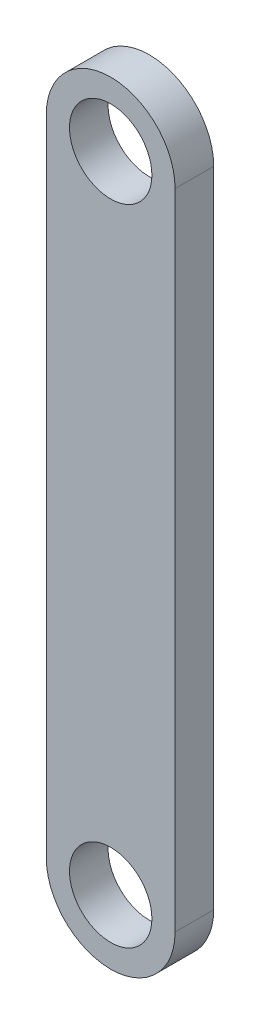
SolidWorks part; units mm, degrees
ref_plane "Plan de face" through (0, 0, 0) normal (0, 0, 1) x (1, 0, 0)
ref_plane "Plan de dessus" through (0, 0, 0) normal (0, 1, 0) x (1, 0, 0)
ref_plane "Plan de droite" through (0, 0, 0) normal (1, 0, 0) x (0, 0, -1)
sketch "Esquisse2" plane through (0, 0, 0) normal (0, 0, 1) x (1, 0, 0)
  line L0 (0, 0) -> (0, 100)
  line L1 (20, 100) -> (20, 0)
  arc A0 (0, 100) -> (20, 100) centre (10, 100) cw
  arc A1 (20, 0) -> (0, 0) centre (10, 0) cw
  circle A2 centre (10, 100) radius 6.4
  circle A3 centre (10, 0) radius 6.4
  dimension "D3" = 12.8
  dimension "D4" = 12.8
  dimension "D1" = 20
  dimension "D2" = 100
extrude "Boss.-Extru.1" add sketch "Esquisse2" along normal blind 6
